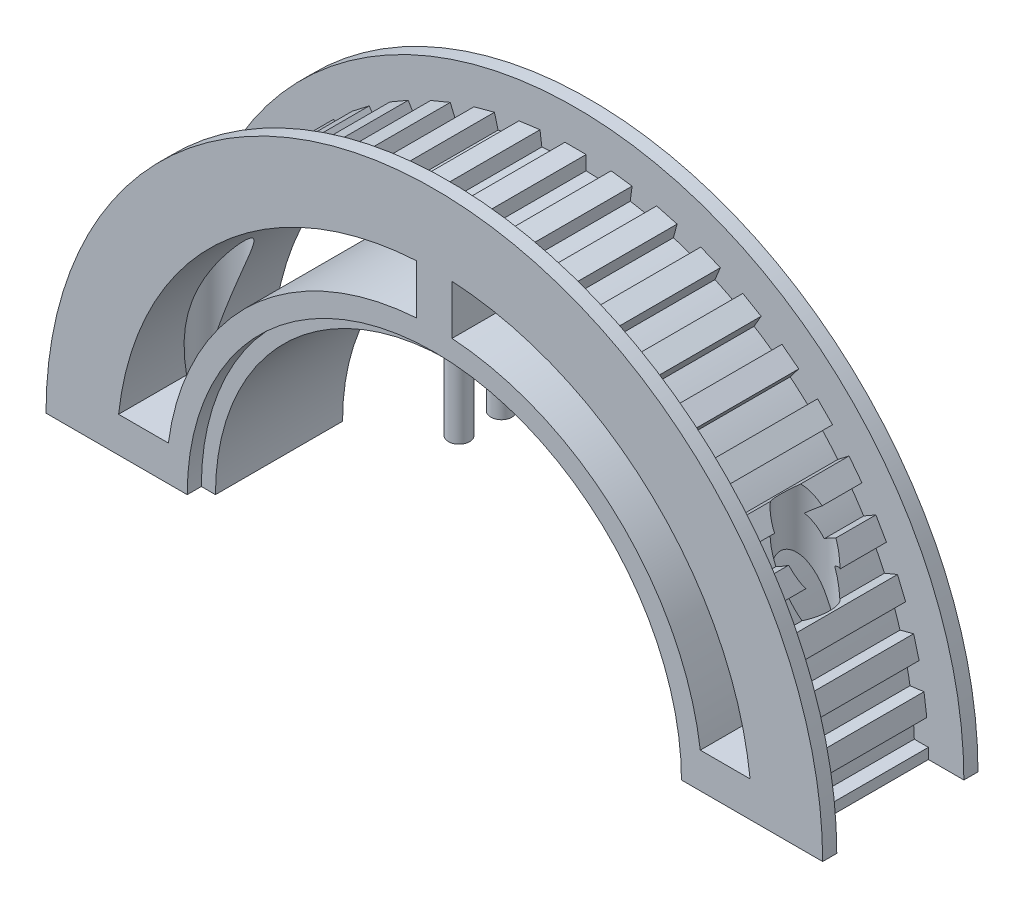
SolidWorks part; units mm, degrees
ref_plane "Front Plane" through (0, 0, 0) normal (0, 0, 1) x (1, 0, 0)
ref_plane "Top Plane" through (0, 0, 0) normal (0, 1, 0) x (1, 0, 0)
ref_plane "Right Plane" through (0, 0, 0) normal (1, 0, 0) x (0, 0, -1)
sketch "Sketch1" plane through (0, 0, 0) normal (0, 0, 1) x (1, 0, 0)
  line L0 (55, 0) -> (-55, 0) construction
  line L5 (0, -55) -> (0, 55) construction
  line L18 (-2.5, 36.9218) -> (2.5, 36.9218)
  line L19 (-2.5, 36.9218) -> (-2.5, 45.9218)
  line L20 (-2.5, 45.9218) -> (2.5, 45.9218)
  line L21 (2.5, 36.9218) -> (2.5, 45.9218)
  line L22 (-45, 0) -> (-48, 0)
  line L23 (45, 0) -> (48, 0)
  line L24 (4.775, 47.7619) -> (5.0361, 49.7448)
  line L29 (-1.5, 47.9766) -> (1.5, 47.9766)
  line L30 (-1.5, 47.9766) -> (-1.5, 49.9766)
  line L31 (-1.5, 49.9766) -> (1.5, 49.9766)
  line L32 (1.5, 47.9766) -> (1.5, 49.9766)
  line L33 (4.775, 47.7619) -> (7.7494, 47.3703)
  line L34 (7.7494, 47.3703) -> (8.0104, 49.3532)
  line L35 (5.0361, 49.7448) -> (8.0104, 49.3532)
  line L36 (10.9684, 46.73) -> (11.486, 48.6619)
  line L37 (10.9684, 46.73) -> (13.8661, 45.9536)
  line L38 (13.8661, 45.9536) -> (14.3838, 47.8854)
  line L39 (11.486, 48.6619) -> (14.3838, 47.8854)
  line L40 (16.974, 44.8986) -> (17.7394, 46.7463)
  line L41 (16.974, 44.8986) -> (19.7457, 43.7505)
  line L42 (19.7457, 43.7505) -> (20.511, 45.5983)
  line L43 (17.7394, 46.7463) -> (20.511, 45.5983)
  line L44 (22.6892, 42.2989) -> (23.6892, 44.031)
  line L45 (22.6892, 42.2989) -> (25.2873, 40.7989)
  line L46 (25.2873, 40.7989) -> (26.2873, 42.531)
  line L47 (23.6892, 44.031) -> (26.2873, 42.531)
  line L48 (28.0162, 38.9755) -> (29.2338, 40.5622)
  line L49 (28.0162, 38.9755) -> (30.3963, 37.1492)
  line L50 (30.3963, 37.1492) -> (31.6138, 38.7359)
  line L51 (29.2338, 40.5622) -> (31.6138, 38.7359)
  line L52 (32.8639, 34.9852) -> (34.2781, 36.3994)
  line L53 (32.8639, 34.9852) -> (34.9852, 32.8639)
  line L54 (34.9852, 32.8639) -> (36.3994, 34.2781)
  line L55 (34.2781, 36.3994) -> (36.3994, 34.2781)
  line L56 (37.1492, 30.3963) -> (38.7359, 31.6138)
  line L57 (37.1492, 30.3963) -> (38.9755, 28.0162)
  line L58 (38.9755, 28.0162) -> (40.5622, 29.2338)
  line L59 (38.7359, 31.6138) -> (40.5622, 29.2338)
  line L60 (40.7989, 25.2873) -> (42.531, 26.2873)
  line L61 (40.7989, 25.2873) -> (42.2989, 22.6892)
  line L62 (42.2989, 22.6892) -> (44.031, 23.6892)
  line L63 (42.531, 26.2873) -> (44.031, 23.6892)
  line L64 (43.7505, 19.7457) -> (45.5983, 20.511)
  line L65 (43.7505, 19.7457) -> (44.8986, 16.974)
  line L66 (44.8986, 16.974) -> (46.7463, 17.7394)
  line L67 (45.5983, 20.511) -> (46.7463, 17.7394)
  line L68 (45.9536, 13.8661) -> (47.8854, 14.3838)
  line L69 (45.9536, 13.8661) -> (46.73, 10.9684)
  line L70 (46.73, 10.9684) -> (48.6619, 11.486)
  line L71 (47.8854, 14.3838) -> (48.6619, 11.486)
  line L72 (47.3703, 7.7494) -> (49.3532, 8.0104)
  line L73 (47.3703, 7.7494) -> (47.7619, 4.775)
  line L74 (47.7619, 4.775) -> (49.7448, 5.0361)
  line L75 (49.3532, 8.0104) -> (49.7448, 5.0361)
  line L80 (-7.7494, 47.3703) -> (-8.0104, 49.3532)
  line L81 (-7.7494, 47.3703) -> (-4.775, 47.7619)
  line L82 (-4.775, 47.7619) -> (-5.0361, 49.7448)
  line L83 (-8.0104, 49.3532) -> (-5.0361, 49.7448)
  line L84 (-13.8661, 45.9536) -> (-14.3838, 47.8854)
  line L85 (-13.8661, 45.9536) -> (-10.9684, 46.73)
  line L86 (-10.9684, 46.73) -> (-11.486, 48.6619)
  line L87 (-14.3838, 47.8854) -> (-11.486, 48.6619)
  line L88 (-19.7457, 43.7505) -> (-20.511, 45.5983)
  line L89 (-19.7457, 43.7505) -> (-16.974, 44.8986)
  line L90 (-16.974, 44.8986) -> (-17.7394, 46.7463)
  line L91 (-20.511, 45.5983) -> (-17.7394, 46.7463)
  line L92 (-25.2873, 40.7989) -> (-26.2873, 42.531)
  line L93 (-25.2873, 40.7989) -> (-22.6892, 42.2989)
  line L94 (-22.6892, 42.2989) -> (-23.6892, 44.031)
  line L95 (-26.2873, 42.531) -> (-23.6892, 44.031)
  line L96 (-30.3963, 37.1492) -> (-31.6138, 38.7359)
  line L97 (-30.3963, 37.1492) -> (-28.0162, 38.9755)
  line L98 (-28.0162, 38.9755) -> (-29.2338, 40.5622)
  line L99 (-31.6138, 38.7359) -> (-29.2338, 40.5622)
  line L100 (-34.9852, 32.8639) -> (-36.3994, 34.2781)
  line L101 (-34.9852, 32.8639) -> (-32.8639, 34.9852)
  line L102 (-32.8639, 34.9852) -> (-34.2781, 36.3994)
  line L103 (-36.3994, 34.2781) -> (-34.2781, 36.3994)
  line L104 (-38.9755, 28.0162) -> (-40.5622, 29.2338)
  line L105 (-38.9755, 28.0162) -> (-37.1492, 30.3963)
  line L106 (-37.1492, 30.3963) -> (-38.7359, 31.6138)
  line L107 (-40.5622, 29.2338) -> (-38.7359, 31.6138)
  line L108 (-42.2989, 22.6892) -> (-44.031, 23.6892)
  line L109 (-42.2989, 22.6892) -> (-40.7989, 25.2873)
  line L110 (-40.7989, 25.2873) -> (-42.531, 26.2873)
  line L111 (-44.031, 23.6892) -> (-42.531, 26.2873)
  line L112 (-44.8986, 16.974) -> (-46.7463, 17.7394)
  line L113 (-44.8986, 16.974) -> (-43.7505, 19.7457)
  line L114 (-43.7505, 19.7457) -> (-45.5983, 20.511)
  line L115 (-46.7463, 17.7394) -> (-45.5983, 20.511)
  line L116 (-46.73, 10.9684) -> (-48.6619, 11.486)
  line L117 (-46.73, 10.9684) -> (-45.9536, 13.8661)
  line L118 (-45.9536, 13.8661) -> (-47.8854, 14.3838)
  line L119 (-48.6619, 11.486) -> (-47.8854, 14.3838)
  line L120 (-47.7619, 4.775) -> (-49.7448, 5.0361)
  line L121 (-47.7619, 4.775) -> (-47.3703, 7.7494)
  line L122 (-47.3703, 7.7494) -> (-49.3532, 8.0104)
  line L123 (-49.7448, 5.0361) -> (-49.3532, 8.0104)
  line L128 (-47.9766, -1.5) -> (-49.9766, -1.5) [skipped]
  line L129 (-49.9766, -1.5) -> (-49.9766, 1.5) [skipped]
  line L130 (-47.9766, 1.5) -> (-49.9766, 1.5) [skipped]
  line L131 (-47.9766, -1.5) -> (-47.9766, 1.5) [skipped]
  line L132 (47.9766, 1.5) -> (49.9766, 1.5) [skipped]
  line L133 (49.9766, 1.5) -> (49.9766, -1.5) [skipped]
  line L134 (47.9766, -1.5) -> (49.9766, -1.5) [skipped]
  line L135 (47.9766, 1.5) -> (47.9766, -1.5) [skipped]
  line L136 (-38, 0) -> (-35, 0)
  line L137 (47.9766, 1.5) -> (49.9766, 1.5)
  line L138 (47.9766, 1.5) -> (47.9766, 0)
  line L139 (47.9766, 0) -> (49.9766, 0)
  line L140 (49.9766, 1.5) -> (49.9766, 0)
  line L141 (-47.9766, 1.5) -> (-49.9766, 1.5)
  line L142 (-47.9766, 1.5) -> (-47.9766, 0)
  line L143 (-47.9766, 0) -> (-49.9766, 0)
  line L144 (-49.9766, 1.5) -> (-49.9766, 0)
  line L145 (35, 0) -> (38, 0)
  line L147 (-45, 0) -> (-37.4718, 0)
  line L148 (-45, 0) -> (-45, 5)
  line L149 (-45, 5) -> (-37.4718, 5)
  line L150 (-37.4718, 0) -> (-37.4718, 5)
  line L151 (45, 0) -> (37.3745, 0)
  line L152 (45, 0) -> (45, 5)
  line L153 (45, 5) -> (37.3745, 5)
  line L154 (37.3745, 0) -> (37.3745, 5)
  arc A2 (-35, 0) -> (35, 0) centre (0, 0) cw
  arc A4 (45, 0) -> (-45, 0) centre (0, 0) ccw
  arc A5 (48, 0) -> (-48, 0) centre (0, 0) ccw
  arc A6 (38, 0) -> (-38, 0) centre (0, 0) ccw
  point P81 (0, 0)
  point P131 (0, 0)
  dimension "D4" = 5
  dimension "D5" = 35
  dimension "D15" = 2
  dimension "D3" = 48
  dimension "D6" = 38
  dimension "D2" = 3
  dimension "D7" = 5
  dimension "D11" = 5
  dimension "D12" = 2.5
  dimension "D14" = 9
  dimension "D16" = 3
  dimension "D17" = 1.5
  dimension "D20" = 1.5
  dimension "D21" = 2
  dimension "D22" = 2
  dimension "D23" = 1.5
  dimension "D18" = 13
  dimension "D19" = 13
extrude "Boss-Extrude1" add sketch "Sketch1" along normal blind 22
sketch "Sketch10" plane through (0, 0, 0) normal (0, -1, 0) x (-1, 0, 0)
  line L0 (35, -22) -> (35, 0) construction
  line L1 (35, -22) -> (49.9766, -22) construction
  circle A0 centre (41.5, -11) radius 1.75
  dimension "D3" = 3.5
  dimension "D1" = 6.5
  dimension "D2" = 11
extrude "Cut-Extrude4" cut sketch "Sketch10" against normal through all
mirror "Mirror4" about plane through (0, 0, 0) normal (1, 0, 0) of "Cut-Extrude4"
sketch "Sketch5" plane through (0, 0, 0) normal (0, 0, 1) x (1, 0, 0)
  line L0 (55, 0) -> (-55, 0) construction
  line L1 (-48, 0) -> (-55, 0)
  line L2 (48, 0) -> (55, 0)
  arc A0 (48, 0) -> (-48, 0) centre (0, 0) ccw
  circle A1 centre (0, 0) radius 48 construction
  arc A2 (55, 0) -> (-55, 0) centre (0, 0) ccw
  dimension "D1" = 55
  dimension "D2" = 7
extrude "Boss-Extrude3" add sketch "Sketch5" along normal blind 2
sketch "Sketch6" plane through (0, 0, 22) normal (0, 0, 1) x (1, 0, 0)
  line L0 (55, 0) -> (-55, 0) construction
  line L1 (-45, 0) -> (-55, 0)
  line L2 (45, 0) -> (55, 0)
  arc A0 (55, 0) -> (-55, 0) centre (0, 0) ccw
  arc A1 (45, 0) -> (-45, 0) centre (0, 0) ccw
  dimension "D1" = 55
  dimension "D2" = 45
extrude "Boss-Extrude4" add sketch "Sketch6" against normal blind 2
ref_plane "Plane1" through (0, 0, 2) normal (0, 0, 1) x (1, 0, 0)
sketch "Sketch7" plane through (0, 0, 2) normal (0, 0, 1) x (1, 0, 0)
  line L0 (55, 0) -> (-55, 0) construction
  line L1 (-35, 0) -> (-33, 0)
  line L2 (33, 0) -> (35, 0)
  arc A0 (35, 0) -> (-35, 0) centre (0, 0) ccw
  arc A1 (33, 0) -> (-33, 0) centre (0, 0) ccw
  dimension "D1" = 35
  dimension "D2" = 33
extrude "Boss-Extrude5" add sketch "Sketch7" along normal blind 18
sketch "Sketch11" plane through (0, 5, 0) normal (0, 1, 0) x (1, 0, 0)
  circle A0 centre (-41.5, -11) radius 3.5
  dimension "D1" = 7
extrude "Cut-Extrude5" cut sketch "Sketch11" along normal through all
mirror "Mirror5" about plane through (0, 0, 0) normal (1, 0, 0) of "Cut-Extrude5"
ref_plane "Plane2" through (0, 33, 0) normal (0, -1, 0) x (-1, 0, 0)
sketch "Sketch14" plane through (0, 33, 0) normal (0, -1, 0) x (-1, 0, 0)
  line L0 (-35, -20) -> (35, -20) construction
  circle A0 centre (0, -18.5) radius 1.5
  circle A1 centre (0, -12.5) radius 1.5
  dimension "D1" = 3
  dimension "D3" = 3
  dimension "D2" = 1.5
  dimension "D4" = 6
extrude "Boss-Extrude6" add sketch "Sketch14" along normal blind 10
sketch "Sketch15" plane through (0, 5, 0) normal (0, 1, 0) x (1, 0, 0)
  line L1 (-41.5, -14.1754) -> (-38.75, -12.5877)
  line L2 (-38.75, -12.5877) -> (-38.75, -9.4123)
  line L3 (-38.75, -9.4123) -> (-41.5, -7.8246)
  line L4 (-41.5, -7.8246) -> (-44.25, -9.4123)
  line L5 (-44.25, -9.4123) -> (-44.25, -12.5877)
  line L6 (-44.25, -12.5877) -> (-41.5, -14.1754)
  circle A0 centre (-41.5, -11) radius 2.75 construction
  dimension "D1" = 5.5
extrude "Cut-Extrude8" cut sketch "Sketch15" against normal blind 2
